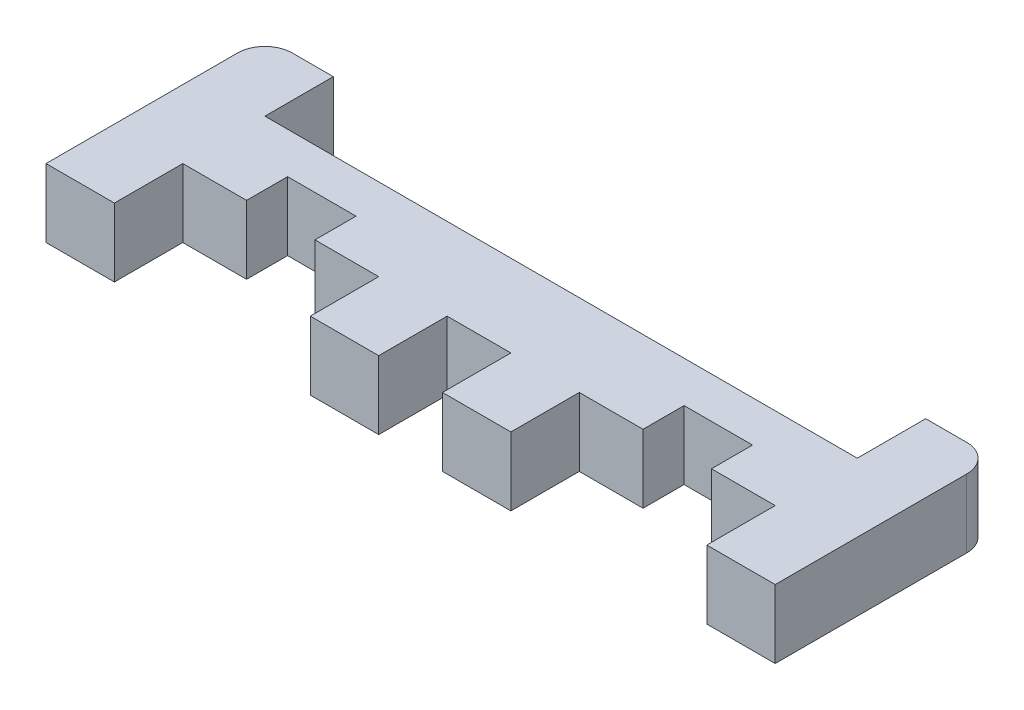
SolidWorks part; units mm, degrees
ref_plane "Front Plane" through (0, 0, 0) normal (0, 0, 1) x (1, 0, 0)
ref_plane "Top Plane" through (0, 0, 0) normal (0, 1, 0) x (1, 0, 0)
ref_plane "Right Plane" through (0, 0, 0) normal (1, 0, 0) x (0, 0, -1)
sketch "Sketch1" plane through (0, 0, 0) normal (0, 1, 0) x (1, 0, 0)
  line L0 (-24.3205, 0) -> (24.3205, 0)
  line L1 (-27.4955, 0) -> (-27.4955, 6.35)
  line L2 (-33.8455, -7.62) -> (-33.8455, 3.81)
  line L3 (-27.4955, 6.35) -> (-31.3055, 6.35)
  line L4 (-27.4955, -7.62) -> (-21.5773, -7.62)
  line L5 (-33.8455, 0) -> (-33.8455, 6.35) construction
  line L6 (27.4955, 6.35) -> (31.3055, 6.35)
  line L7 (0, 0) -> (0, -7.62) construction
  line L8 (33.8455, -13.97) -> (33.8455, 3.81)
  line L9 (-24.3205, 0) -> (-27.4955, 0)
  line L10 (-33.8455, -7.62) -> (-33.8455, -13.97)
  line L11 (27.4955, -13.97) -> (33.8455, -13.97)
  line L12 (-27.4955, -13.97) -> (-27.4955, -7.62)
  line L13 (15.2273, -3.81) -> (15.2273, -7.62)
  line L14 (-15.2273, -3.81) -> (-21.5773, -3.81)
  line L15 (-21.5773, -3.81) -> (-21.5773, -7.62)
  line L16 (-2.9591, -13.97) -> (-2.9591, -7.62)
  line L17 (2.9591, -13.97) -> (9.3091, -13.97)
  line L18 (-9.3091, -7.62) -> (-9.3091, -13.97)
  line L19 (9.3091, -13.97) -> (9.3091, -7.62)
  line L20 (-9.3091, -13.97) -> (-2.9591, -13.97)
  line L21 (2.9591, -7.62) -> (2.9591, -13.97)
  line L22 (-15.2273, -3.81) -> (-15.2273, -7.62)
  line L23 (-15.2273, -7.62) -> (-9.3091, -7.62)
  line L24 (21.5773, -3.81) -> (21.5773, -7.62)
  line L25 (-33.8455, -13.97) -> (-27.4955, -13.97)
  line L26 (15.2273, -3.81) -> (21.5773, -3.81)
  line L27 (27.4955, -7.62) -> (27.4955, -13.97)
  line L28 (15.2273, -7.62) -> (9.3091, -7.62)
  line L30 (-2.9591, -7.62) -> (2.9591, -7.62)
  line L32 (33.8455, -10.795) -> (33.8455, -7.62) [skipped]
  line L34 (-27.4955, 0) -> (-27.4955, 6.35) construction
  line L35 (27.4955, -7.62) -> (21.5773, -7.62)
  line L38 (27.4955, 0) -> (27.4955, 6.35)
  line L39 (24.3205, 0) -> (27.4955, 0)
  line L52 (-15.2273, -13.97) -> (-15.2273, -7.62) [skipped]
  line L53 (-21.5773, -7.62) -> (-21.5773, -13.97) [skipped]
  line L54 (21.5773, -13.97) -> (21.5773, -7.62) [skipped]
  line L55 (15.2273, -7.62) -> (15.2273, -13.97) [skipped]
  arc A0 (-33.8455, 3.81) -> (-31.3055, 6.35) centre (-31.3055, 3.81) cw
  arc A1 (33.8455, 3.81) -> (31.3055, 6.35) centre (31.3055, 3.81) ccw
  point P14 (-18.4023, -7.62)
  dimension "D3" = 2.54
  dimension "D1" = 7.62
  dimension "D4" = 6.35
  dimension "D7" = 6
extrude "Boss-Extrude1" add sketch "Sketch1" along normal blind 6.35
